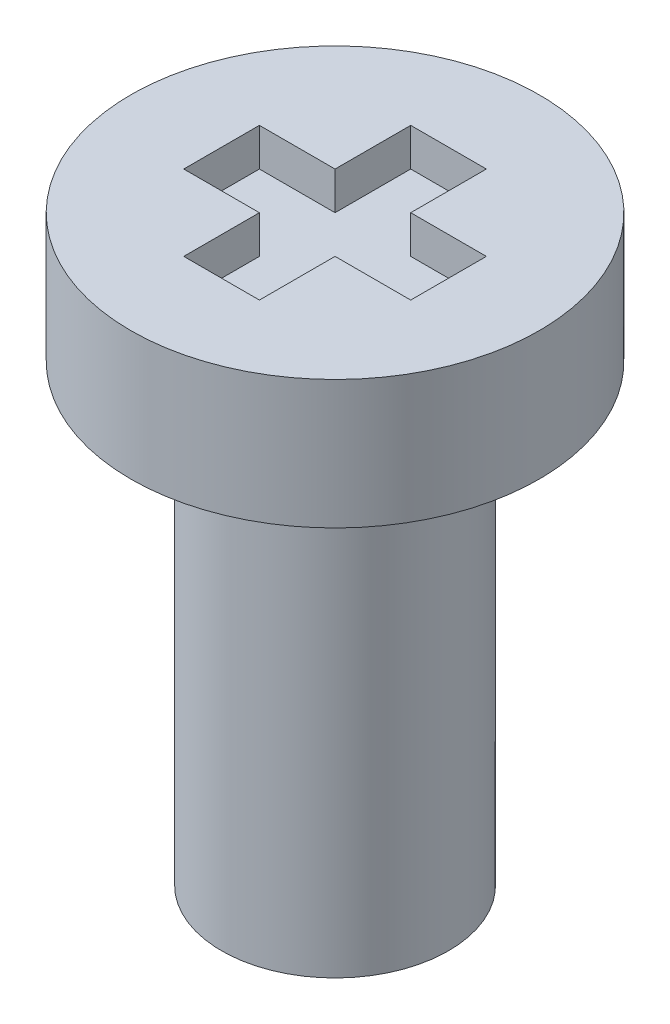
SolidWorks part; units mm, degrees
material "1060 合金"
ref_plane "前视基准面" through (0, 0, 0) normal (0, 0, 1) x (1, 0, 0)
ref_plane "上视基准面" through (0, 0, 0) normal (0, 1, 0) x (1, 0, 0)
ref_plane "右视基准面" through (0, 0, 0) normal (1, 0, 0) x (0, 0, -1)
other "Configuration Table"
sketch "草图1" plane through (0, 0, 0) normal (0, 1, 0) x (1, 0, 0)
  circle A0 centre (0, 0) radius 2.7
extrude "凸台-拉伸1" add sketch "草图1" along normal blind 1.7
sketch "草图2" plane through (0, 1.7, 0) normal (0, 1, 0) x (1, 0, 0)
  line L0 (0, 0) -> (0, 1.921) construction
  line L1 (0, 1.921) -> (0, -2.1424) construction
  line L2 (-1.7353, 0) -> (1.7128, 0) construction
  line L3 (0, 1.5) -> (0.5, 1.5)
  line L4 (0, 1.5) -> (-0.5, 1.5)
  line L5 (-1.5, 0) -> (-1.5, 0.5)
  line L6 (-1.5, 0) -> (-1.5, -0.5)
  line L7 (0, -1.5) -> (-0.5, -1.5)
  line L9 (0.5, -1.5) -> (0, -1.5)
  line L10 (1.5, 0) -> (1.5, 0.5)
  line L12 (1.5, -0.5) -> (1.5, 0)
  line L13 (1.5, -0.5) -> (0.5, -0.5)
  line L14 (0.5, -0.5) -> (0.5, -1.5)
  line L15 (-0.5, -1.5) -> (-0.5, -0.5)
  line L16 (-0.5, -0.5) -> (-1.5, -0.5)
  line L17 (-1.5, 0.5) -> (-0.5, 0.5)
  line L18 (-0.5, 0.5) -> (-0.5, 1.5)
  line L19 (0.5, 1.5) -> (0.5, 0.5)
  line L20 (0.5, 0.5) -> (1.5, 0.5)
  point P3 (0, 1.5)
  point P7 (0, -1.5)
  point P8 (1.5, 0)
  point P9 (-1.5, 0)
  dimension "D1" = 1.5
  dimension "D2" = 1.5
  dimension "D3" = 1.5
  dimension "D4" = 1.5
  dimension "D5" = 0.5
  dimension "D6" = 0.5
extrude "切除-拉伸1" cut sketch "草图2" against normal blind 0.5
sketch "草图3" plane through (0, 0, 0) normal (0, -1, 0) x (1, 0, 0)
  circle A0 centre (0, 0) radius 1.5
extrude "凸台-拉伸2" add sketch "草图3" along normal blind 6
